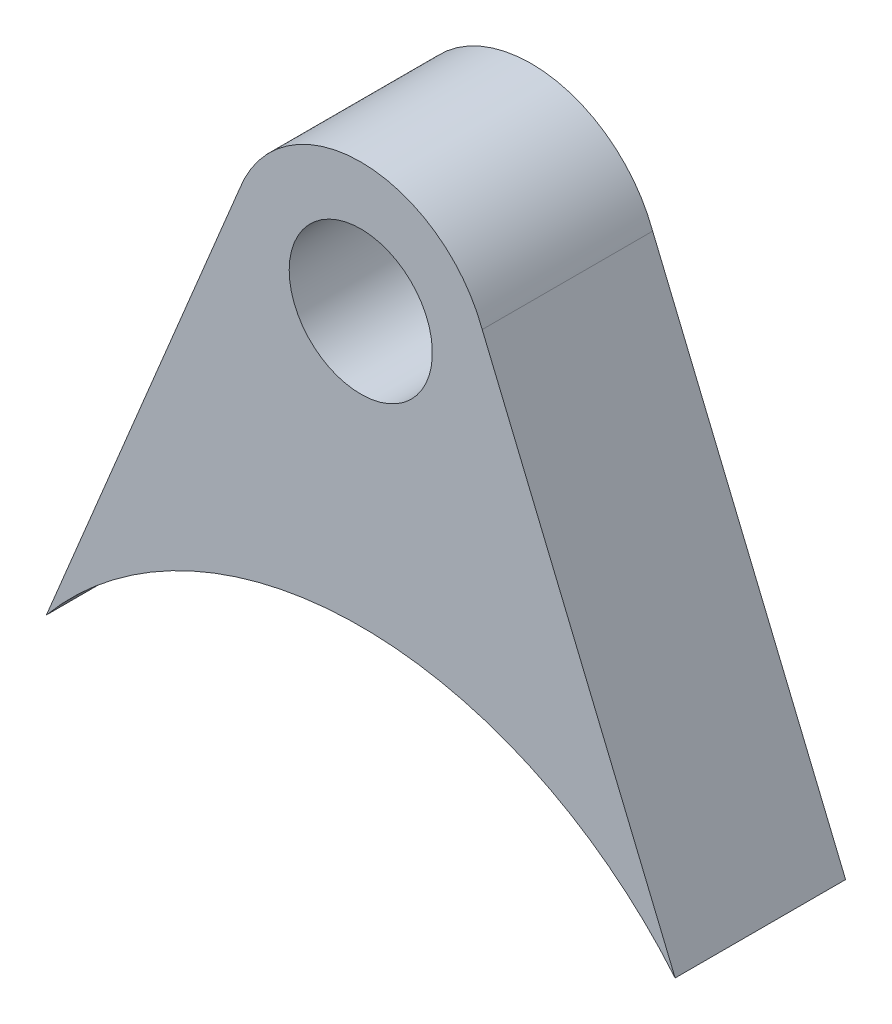
SolidWorks part; units mm, degrees
material "一般"
ref_plane "Płaszczyzna przednia" through (0, 0, 0) normal (0, 0, 1) x (1, 0, 0)
ref_plane "Płaszczyzna górna" through (0, 0, 0) normal (0, 1, 0) x (1, 0, 0)
ref_plane "Płaszczyzna prawa" through (0, 0, 0) normal (1, 0, 0) x (0, 0, -1)
ref_plane "Płaszczyzna1" through (2.0734, -5.6966, 0) normal (-0.9397, -0.342, 0) x (0, 0, 1)
ref_plane "Płaszczyzna2" through (0, 0, 0) normal (0.342, -0.9397, 0) x (-0.9397, -0.342, 0)
ref_plane "Płaszczyzna3" through (0, 7.5, 0) normal (0, 1, 0) x (1, 0, 0)
ref_plane "Płaszczyzna4" through (15, 0, 0) normal (1, 0, 0) x (0, 0, -1)
sketch "Szkic2" plane through (0, 0, 16.9) normal (0, 0, -1) x (-1, 0, 0)
  line L0 (0, 14) -> (0, 18)
  line L1 (9.2222, 7.6779) -> (-9.2222, 7.6779)
  line L2 (-9.2222, 7.6779) -> (-3.5624, 21.3227)
  line L3 (9.2222, 7.6779) -> (3.5624, 21.3227)
  line L6 (0, 0) -> (6.368, 0)
  line L13 (0, 0) -> (0, 20)
  circle A8 centre (0, 20) radius 2.1
  circle A11 centre (0, 20) radius 3.8
  circle A12 centre (0, 0) radius 12 construction
  circle A14 centre (0, 0) radius 12
extrude "Dodanie-wyciągnięcie1" add sketch "Szkic2" against normal blind 5 from offset 9.7
